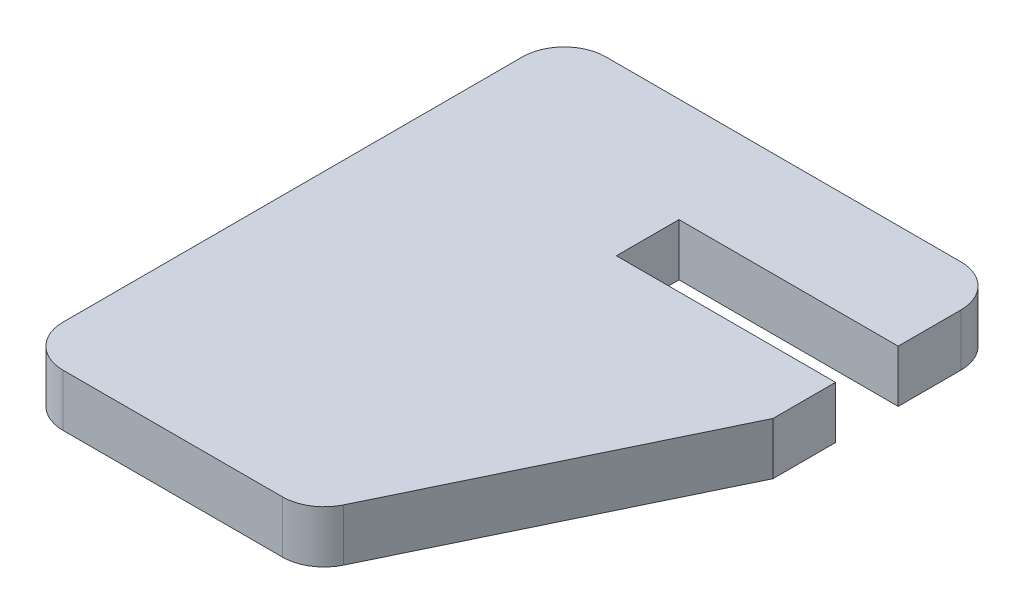
SolidWorks part; units mm, degrees
ref_plane "Front Plane" through (0, 0, 0) normal (0, 0, 1) x (1, 0, 0)
ref_plane "Top Plane" through (0, 0, 0) normal (0, 1, 0) x (1, 0, 0)
ref_plane "Right Plane" through (0, 0, 0) normal (1, 0, 0) x (0, 0, -1)
sketch "Sketch1" plane through (0, 0, 0) normal (0, 1, 0) x (1, 0, 0)
  line L0 (26.67, 7.62) -> (26.67, 15.24)
  line L1 (-21.59, -45.72) -> (5.08, -45.72)
  line L2 (-26.67, -40.64) -> (-26.67, 15.24)
  line L3 (-21.59, 20.32) -> (21.59, 20.32)
  line L4 (26.67, -7.62) -> (26.67, 0)
  line L7 (26.67, 7.62) -> (0, 7.62)
  line L8 (26.67, -7.62) -> (9.6544, -42.8494)
  line L9 (26.67, 0) -> (0, 0)
  line L10 (0, 7.62) -> (0, 0)
  arc A0 (9.6544, -42.8494) -> (5.08, -45.72) centre (5.08, -40.64) cw
  arc A1 (-21.59, -45.72) -> (-26.67, -40.64) centre (-21.59, -40.64) cw
  arc A2 (21.59, 20.32) -> (26.67, 15.24) centre (21.59, 15.24) cw
  arc A3 (-26.67, 15.24) -> (-21.59, 20.32) centre (-21.59, 15.24) cw
  point P0 (0, 0)
  point P14 (8.2679, -45.72)
  point P25 (0, 0)
  dimension "D9" = 5.08
  dimension "D4" = 55.88
  dimension "D1" = 26.67
  dimension "D2" = 7.62
  dimension "D3" = 7.62
  dimension "D5" = 31.75
  dimension "D6" = 7.62
extrude "Boss-Extrude1" add sketch "Sketch1" along normal blind 6.35
